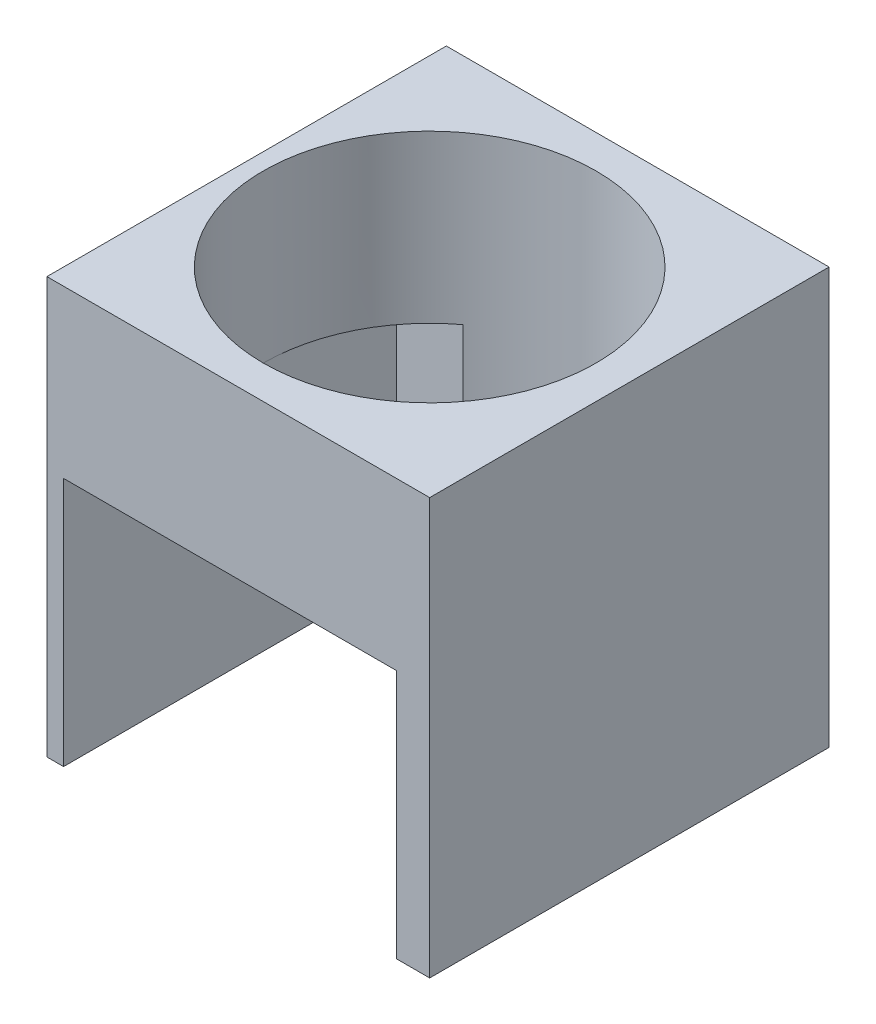
SolidWorks part; units mm, degrees
ref_plane "정면" through (0, 0, 0) normal (0, 0, 1) x (1, 0, 0)
ref_plane "윗면" through (0, 0, 0) normal (0, 1, 0) x (1, 0, 0)
ref_plane "우측면" through (0, 0, 0) normal (1, 0, 0) x (0, 0, -1)
sketch "Sketch1" plane through (0, 0, 0) normal (0, 1, 0) x (1, 0, 0)
  line L1 (0, 0) -> (670, 0)
  line L2 (0, 0) -> (0, 120)
  line L3 (0, 120) -> (670, 120)
  line L4 (670, 0) -> (670, 120)
  dimension "700" = 670
  dimension "D2" = 120
extrude "Boss-Extrude1" add sketch "Sketch1" along normal blind 530
sketch "Sketch2" plane through (0, 0, 0) normal (0, 0, 1) x (1, 0, 0)
  line L0 (0, 530) -> (0, 0) construction
  line L1 (10, 280) -> (110, 280)
  line L2 (10, 280) -> (10, 480)
  line L3 (10, 480) -> (110, 480)
  line L4 (110, 280) -> (110, 480)
  line L5 (0, 0) -> (670, 0) construction
  line L6 (120, 280) -> (120, 480)
  line L7 (120, 280) -> (220, 280)
  line L8 (220, 280) -> (220, 480)
  line L9 (120, 480) -> (220, 480)
  line L10 (230, 280) -> (230, 480)
  line L11 (230, 280) -> (330, 280)
  line L12 (330, 280) -> (330, 480)
  line L13 (230, 480) -> (330, 480)
  line L14 (340, 280) -> (340, 480)
  line L15 (340, 280) -> (440, 280)
  line L16 (440, 280) -> (440, 480)
  line L17 (340, 480) -> (440, 480)
  line L18 (450, 280) -> (450, 480)
  line L19 (450, 280) -> (550, 280)
  line L20 (550, 280) -> (550, 480)
  line L21 (450, 480) -> (550, 480)
  line L22 (560, 280) -> (560, 480)
  line L23 (560, 280) -> (660, 280)
  line L24 (660, 280) -> (660, 480)
  line L25 (560, 480) -> (660, 480)
  line L27 (10, 10) -> (660, 10)
  line L28 (10, 10) -> (10, 260)
  line L29 (10, 260) -> (660, 260)
  line L30 (660, 10) -> (660, 260)
  line L31 (0, 530) -> (670, 530) construction
  point P6 (10, 380)
  dimension "D1" = 100
  dimension "D2" = 200
  dimension "D3" = 10
  dimension "D4" = 50
  dimension "D6" = 10
  dimension "D7" = 20
  dimension "D5" = 6
extrude "Cut-Extrude1" cut sketch "Sketch2" against normal blind 100
sketch "Sketch3" plane through (0, 530, 0) normal (0, 1, 0) x (1, 0, 0)
  line L1 (670, 120) -> (0, 120) construction
  line L2 (0, 120) -> (0, 0) construction
  circle A0 centre (60, 60) radius 50
  circle A1 centre (170, 60) radius 50
  circle A2 centre (280, 60) radius 50
  circle A3 centre (390, 60) radius 50
  circle A4 centre (500, 60) radius 50
  circle A5 centre (610, 60) radius 50
  dimension "D1" = 100
  dimension "D2" = 10
  dimension "D3" = 10
  dimension "D4" = 6
extrude "Cut-Extrude2" cut sketch "Sketch3" against normal blind 260
hole_wizard "Ø12.0 (12) Diameter Hole2" positions "3DSketch1" profile "Sketch7" hole size "Ø12.0" standard "Ansi Metric"
sketch3d "3DSketch1"
  point P0 (59.7046, 270, -102.4117)
  point P2 (171.5567, 270, -102.6076)
  point P4 (280.8723, 270, -102.3969)
  point P6 (391.0687, 270, -102.7535)
  point P8 (500.7133, 270, -101.754)
  point P10 (609.5165, 270, -101.1227)
sketch "Sketch7" plane through (59.7046, 270, -102.4117) normal (1, 0, 0) x (0, 0, 1)
  line L0 (0, 0) -> (0, 33.6052)
  line L1 (0, 33.6052) -> (6, 30)
  line L2 (6, 30) -> (6, 0)
  line L5 (6, 0) -> (0, 0)
  line L10 (0, 33.6052) -> (-6, 30) construction
  line L11 (0, -6.35) -> (0, 107.95) construction
  dimension "구멍 지름" = 12
  dimension "구멍 깊이" = 30
  dimension "드릴 각도" = 118
sketch "Sketch8" plane through (0, 0, 0) normal (0, 0, 1) x (1, 0, 0)
  line L0 (660, 280) -> (660, 480) construction
  line L1 (10, 280) -> (660, 280)
  line L2 (10, 280) -> (10, 330)
  line L3 (10, 330) -> (660, 330)
  line L4 (660, 280) -> (660, 330)
  dimension "D1" = 50
extrude "Boss-Extrude2" add sketch "Sketch8" against normal blind 5
sketch "Sketch9" plane through (670, 0, 0) normal (1, 0, 0) x (0, 0, -1)
  line L0 (0, 530) -> (0, 0) construction
  line L1 (10, 10) -> (20, 10)
  line L2 (10, 10) -> (10, 260)
  line L3 (10, 260) -> (20, 260)
  line L4 (20, 10) -> (20, 260)
  line L5 (0, 0) -> (120, 0) construction
  dimension "D1" = 10
  dimension "D2" = 10
  dimension "D3" = 10
  dimension "D4" = 250
extrude "Cut-Extrude3" cut sketch "Sketch9" against normal blind 717
sketch "Sketch10" plane through (0, 10, 0) normal (0, 1, 0) x (1, 0, 0)
  line L0 (670, 120) -> (0, 120) construction
  line L1 (365, 61.9436) -> (350, 87.9243)
  line L2 (350, 87.9243) -> (320, 87.9243)
  line L3 (320, 87.9243) -> (305, 61.9436)
  line L4 (305, 61.9436) -> (320, 35.9628)
  line L5 (320, 35.9628) -> (350, 35.9628)
  line L6 (350, 35.9628) -> (365, 61.9436)
  line L7 (0, 120) -> (0, 0) construction
  circle A0 centre (335, 61.9436) radius 25.9808 construction
  dimension "D1" = 60
  dimension "D2" = 305
extrude "Cut-Extrude4" cut sketch "Sketch10" against normal blind 5
sketch "Sketch11" plane through (0, 0, -100) normal (0, 0, 1) x (1, 0, 0)
  line L0 (10, 10) -> (660, 10) construction
  line L1 (250, 10) -> (260, 10)
  line L2 (250, 10) -> (250, 110)
  line L3 (250, 110) -> (260, 110)
  line L4 (260, 10) -> (260, 110)
  line L5 (660, 10) -> (660, 260) construction
  line L6 (410, 10) -> (420, 10)
  line L7 (410, 10) -> (410, 110)
  line L8 (410, 110) -> (420, 110)
  line L9 (420, 10) -> (420, 110)
  line L10 (25, 198.4569) -> (325, 145.5588)
  line L11 (325, 145.5588) -> (325, 122.0178)
  line L12 (325, 122.0178) -> (345, 122.0178)
  line L13 (345, 122.0178) -> (345, 145.5588)
  line L14 (345, 145.5588) -> (645, 198.4569)
  line L15 (645, 198.4569) -> (25, 198.4569)
  point P18 (345, 133.7883)
  dimension "D1" = 10
  dimension "D2" = 10
  dimension "D3" = 100
  dimension "D4" = 100
  dimension "D5" = 150
  dimension "D6" = 240
  dimension "D7" = 20
  dimension "D8" = 65
  dimension "D9" = 100
  dimension "D10" = 620
  dimension "D11" = 100
extrude "Boss-Extrude3" add sketch "Sketch11" along normal blind 78 separate body
sketch "Sketch12" plane through (0, 0, -100) normal (0, 0, 1) x (1, 0, 0)
  line L0 (660, 260) -> (10, 260) construction
  line L1 (75.1986, 260) -> (95.1986, 260)
  line L2 (75.1986, 260) -> (75.1986, 230)
  line L3 (75.1986, 230) -> (95.1986, 230)
  line L4 (95.1986, 260) -> (95.1986, 230)
  line L5 (65.1986, 260) -> (65.1986, 240) construction
  line L6 (185.1986, 260) -> (185.1986, 230)
  line L7 (185.1986, 260) -> (205.1986, 260)
  line L8 (205.1986, 260) -> (205.1986, 230)
  line L9 (185.1986, 230) -> (205.1986, 230)
  line L10 (295.1986, 260) -> (295.1986, 230)
  line L11 (295.1986, 260) -> (315.1986, 260)
  line L12 (315.1986, 260) -> (315.1986, 230)
  line L13 (295.1986, 230) -> (315.1986, 230)
  line L14 (405.1986, 260) -> (405.1986, 230)
  line L15 (405.1986, 260) -> (425.1986, 260)
  line L16 (425.1986, 260) -> (425.1986, 230)
  line L17 (405.1986, 230) -> (425.1986, 230)
  line L18 (515.1986, 260) -> (515.1986, 230)
  line L19 (515.1986, 260) -> (535.1986, 260)
  line L20 (535.1986, 260) -> (535.1986, 230)
  line L21 (515.1986, 230) -> (535.1986, 230)
  line L22 (625.1986, 260) -> (625.1986, 230)
  line L23 (625.1986, 260) -> (645.1986, 260)
  line L24 (645.1986, 260) -> (645.1986, 230)
  line L25 (625.1986, 230) -> (645.1986, 230)
  dimension "D1" = 20
  dimension "D2" = 30
  dimension "D3" = 10
  dimension "D4" = 6
extrude "Cut-Extrude5" cut sketch "Sketch12" against normal blind 80
sketch "Sketch15" plane through (345, 0, 0) normal (1, 0, 0) x (0, 0, -1)
  line L0 (20, 10) -> (20, 260) construction
  line L1 (20, 121.4638) -> (50, 121.4638)
  line L2 (20, 121.4638) -> (20, 145)
  line L3 (20, 145) -> (50, 145)
  line L4 (50, 121.4638) -> (50, 145)
  line L5 (120, 530) -> (120, 0) construction
  line L6 (100, 116.0134) -> (70, 116.0134)
  line L7 (100, 116.0134) -> (100, 145)
  line L8 (100, 145) -> (70, 145)
  line L9 (70, 116.0134) -> (70, 145)
  line L10 (20, 260) -> (10, 260) construction
  dimension "D1" = 20
  dimension "D2" = 20
  dimension "D3" = 115
  dimension "D4" = 30
extrude "Cut-Extrude7" cut sketch "Sketch15" against normal blind 35
shell "Shell1" thickness 3
sketch "Sketch16" plane through (0, 122.0178, 0) normal (0, -1, 0) x (1, 0, 0)
  line L0 (345, -50) -> (325, -50) construction
  line L1 (328, -53) -> (342, -53)
  line L2 (328, -53) -> (328, -67)
  line L3 (328, -67) -> (342, -67)
  line L4 (342, -53) -> (342, -67)
  line L5 (325, -50) -> (325, -70) construction
  line L6 (345, -50) -> (345, -70) construction
  line L7 (325, -70) -> (345, -70) construction
  dimension "D1" = 3
  dimension "D2" = 3
  dimension "D3" = 3
  dimension "D4" = 3
extrude "Cut-Extrude8" cut sketch "Sketch16" against normal blind 35
sketch "Sketch17" plane through (0, 0, 0) normal (0, 0, 1) x (1, 0, 0)
  text T0 "<b>DIFF_USER</b>" font "Britannic Bold" height in points 72
extrude "Boss-Extrude4" add sketch "Sketch17" along normal blind 5
sketch "Sketch18" plane through (0, 0, 0) normal (0, 0, 1) x (1, 0, 0)
  line L0 (670, 530) -> (670, 0) construction
  line L1 (0, 0) -> (670, 0)
  line L2 (0, 0) -> (0, 280)
  line L3 (0, 280) -> (670, 280)
  line L4 (670, 0) -> (670, 280)
  dimension "D1" = 280
extrude "Cut-Extrude10" cut sketch "Sketch18" against normal blind 159
sketch "Sketch19" plane through (0, 0, 0) normal (0, 0, 1) x (1, 0, 0)
  line L0 (670, 280) -> (0, 280) construction
  line L1 (670, 280) -> (555, 280)
  line L2 (670, 280) -> (670, 530)
  line L3 (670, 530) -> (555, 530)
  line L4 (555, 280) -> (555, 530)
  line L5 (0, 530) -> (670, 530) construction
  line L6 (670, 530) -> (670, 280) construction
  line L8 (0, 530) -> (555, 530)
  line L9 (0, 530) -> (0, 280)
  line L10 (0, 280) -> (555, 280)
  line L11 (555, 530) -> (555, 280)
  dimension "D1" = 115
extrude "Cut-Extrude12" cut sketch "Sketch19" against normal blind 135 and the other way blind 59 contours L9 L10 L4 L8
sketch "Sketch20" plane through (0, 0, 0) normal (0, 0, 1) x (1, 0, 0)
  line L0 (670, 530) -> (670, 280) construction
  line L1 (555, 280) -> (670, 280)
  line L2 (555, 280) -> (555, 405)
  line L3 (555, 405) -> (670, 405)
  line L4 (670, 280) -> (670, 405)
extrude "Cut-Extrude13" cut sketch "Sketch20" against normal through all both and the other way through all
